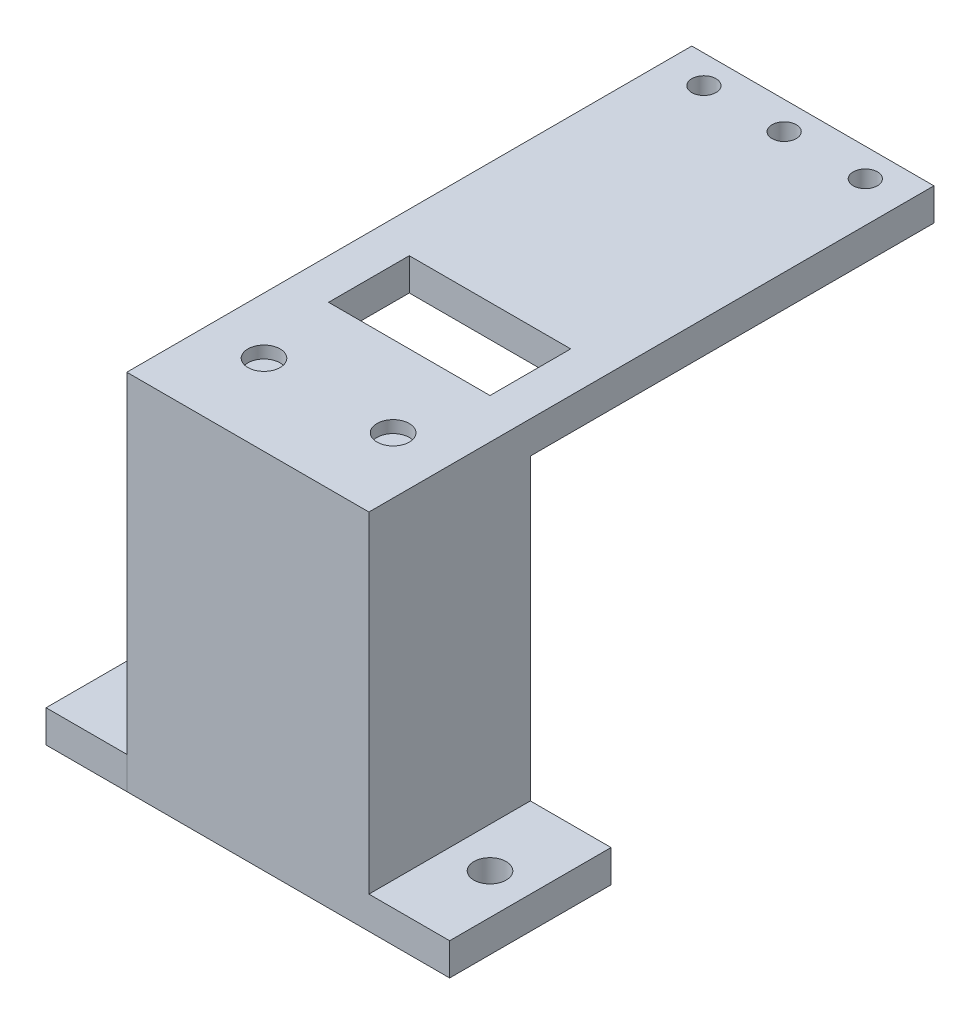
SolidWorks part; units mm, degrees
ref_plane "Front Plane" through (0, 0, 0) normal (0, 0, 1) x (1, 0, 0)
ref_plane "Top Plane" through (0, 0, 0) normal (0, 1, 0) x (1, 0, 0)
ref_plane "Right Plane" through (0, 0, 0) normal (1, 0, 0) x (0, 0, -1)
sketch "Sketch1" plane through (0, 0, 0) normal (0, 1, 0) x (1, 0, 0)
  line L1 (0, 0) -> (30, 0)
  line L2 (0, 0) -> (0, 20)
  line L3 (0, 20) -> (30, 20)
  line L4 (30, 0) -> (30, 20)
extrude "Boss-Extrude1" add sketch "Sketch1" along normal blind 45
sketch "Sketch3" plane through (0, 0, 0) normal (0, -1, 0) x (1, 0, 0)
  line L1 (30, 0) -> (40, 0)
  line L2 (30, 0) -> (30, -20)
  line L3 (30, -20) -> (40, -20)
  line L4 (40, 0) -> (40, -20)
  dimension "D1" = 10
extrude "Boss-Extrude2" add sketch "Sketch3" against normal blind 4
sketch "Sketch4" plane through (0, 0, 0) normal (0, -1, 0) x (-1, 0, 0)
  line L1 (0, 0) -> (10, 0)
  line L2 (0, 0) -> (0, 20)
  line L3 (0, 20) -> (10, 20)
  line L4 (10, 0) -> (10, 20)
  dimension "D1" = 10
  dimension "D2" = 20
extrude "Boss-Extrude3" add sketch "Sketch4" against normal blind 4 separate body contours L2 L1 L4 L3
sketch "Sketch5" plane through (0, 0, 0) normal (0, -1, 0) x (1, 0, 0)
  line L0 (40, 0) -> (35, 0)
  line L2 (0, 0) -> (40, 0) construction
  circle A0 centre (-5, -10) radius 2
  circle A1 centre (35, -10) radius 2
extrude "Cut-Extrude2" cut sketch "Sketch5" against normal blind 4 contours A1 | A0
sketch "Sketch8" plane through (0, 45, 0) normal (0, 1, 0) x (1, 0, 0)
  line L2 (30, 20) -> (15, 20)
  line L3 (30, 20) -> (30, 10)
  line L6 (0, 20) -> (0, 0) construction
  line L7 (30, 0) -> (30, 20) construction
  circle A0 centre (7, 10) radius 2
  circle A1 centre (23, 10) radius 2
  dimension "D1" = 7
  dimension "D2" = 7
  dimension "D3" = 16
extrude "Cut-Extrude3" cut sketch "Sketch8" against normal blind 1.5 contours A0 | A1
sketch "Sketch9" plane through (0, 0, -20) normal (0, 0, -1) x (-1, 0, 0)
  line L0 (-30, 45) -> (-30, 4) construction
  line L1 (0, 45) -> (-30, 45)
  line L2 (0, 45) -> (0, 41)
  line L3 (0, 41) -> (-30, 41)
  line L4 (-30, 45) -> (-30, 41)
  dimension "D1" = 4
extrude "Boss-Extrude4" add sketch "Sketch9" along normal blind 50
sketch "Sketch10" plane through (0, 45, 0) normal (0, 1, 0) x (1, 0, 0)
  line L0 (25, 30) -> (5, 30)
  line L3 (5, 30) -> (5, 20)
  line L4 (5, 20) -> (25, 20)
  line L6 (25, 30) -> (25, 20)
extrude "Cut-Extrude4" cut sketch "Sketch10" against normal blind 4
sketch "Sketch11" plane through (0, 45, 0) normal (0, 1, 0) x (1, 0, 0)
  circle A0 centre (25, 66.5) radius 1.5
  circle A2 centre (14.9116, 66.5329) radius 1.5
  circle A3 centre (5, 66.5) radius 1.5
extrude "Cut-Extrude5" cut sketch "Sketch11" against normal blind 4 contours A0 | A2 | A3
